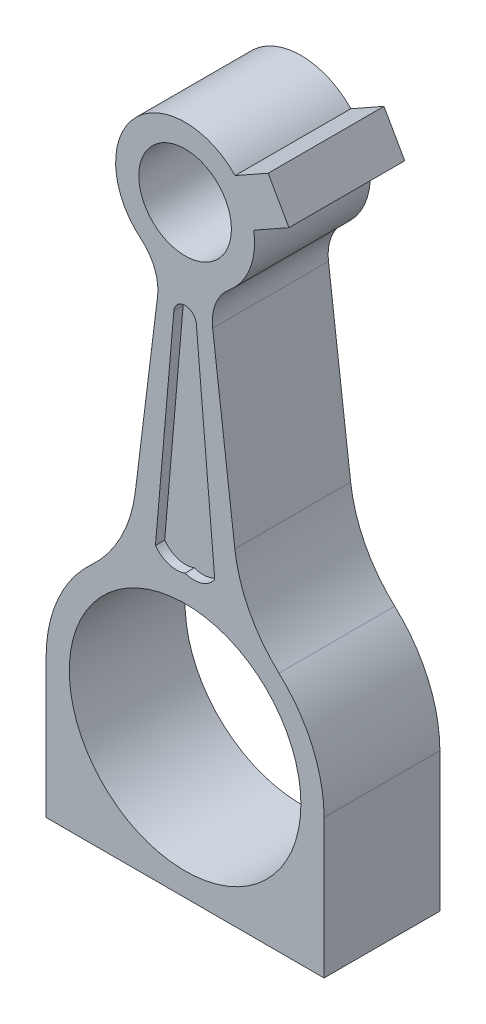
SolidWorks part; units mm, degrees
ref_plane "Front Plane" through (0, 0, 0) normal (0, 0, 1) x (1, 0, 0)
ref_plane "Top Plane" through (0, 0, 0) normal (0, 1, 0) x (1, 0, 0)
ref_plane "Right Plane" through (0, 0, 0) normal (1, 0, 0) x (0, 0, -1)
sketch "Sketch1" plane through (0, 0, 0) normal (0, 0, 1) x (1, 0, 0)
  line L0 (0, 0) -> (0, 100) construction
  line L1 (-5.9496, 79.4649) -> (-10.7353, 40.5936)
  line L2 (5.9496, 79.4649) -> (10.7353, 40.5936)
  line L3 (10.7954, 110.4144) -> (17.9357, 114.4279)
  line L5 (-30, 0) -> (-30, -30)
  line L6 (-30, -30) -> (30, -30)
  line L7 (30, 0) -> (30, -30)
  line L9 (17.9357, 114.4279) -> (22.4152, 106.4804)
  line L10 (14.8349, 102.2196) -> (22.4152, 106.4804)
  circle A0 centre (0, 0) radius 25
  arc A1 (-20.2553, 22.1297) -> (-30, 0) centre (0, 0) ccw
  circle A2 centre (0, 100) radius 10
  arc A3 (9.5248, 88.4121) -> (14.8349, 102.2196) centre (0, 100) ccw
  arc A4 (-5.9496, 79.4649) -> (-9.5248, 88.4121) centre (-15.8746, 80.6869) ccw
  arc A5 (-10.7353, 40.5936) -> (-20.2553, 22.1297) centre (-40.5105, 44.2594) cw
  arc A6 (10.7353, 40.5936) -> (20.2553, 22.1297) centre (40.5105, 44.2594) ccw
  arc A7 (5.9496, 79.4649) -> (9.5248, 88.4121) centre (15.8746, 80.6869) cw
  arc A8 (30, 0) -> (20.2553, 22.1297) centre (0, 0) ccw
  arc A9 (10.7954, 110.4144) -> (-9.5248, 88.4121) centre (0, 100) ccw
  dimension "D1" = 50
  dimension "D2" = 30
  dimension "D4" = 20
  dimension "D5" = 30
  dimension "D6" = 10
  dimension "D7" = 30
  dimension "D3" = 100
  dimension "D8" = 60
extrude "Boss-Extrude1" add sketch "Sketch1" along normal blind 25
sketch "Sketch2" plane through (0, 0, 25) normal (0, 0, 1) x (1, 0, 0)
  line L0 (-2.424, 78.5189) -> (-6.4034, 32.6767)
  line L1 (0, 93.5568) -> (0, 17.9011) construction
  line L2 (2.424, 78.5189) -> (6.4034, 32.6767)
  arc A0 (-6.4034, 32.6767) -> (0, 30.677) centre (-1.8817, 35.9038) ccw
  arc A1 (-2.424, 78.5189) -> (2.424, 78.5189) centre (0, 78.3083) cw
  arc A2 (6.4034, 32.6767) -> (0, 30.677) centre (1.8817, 35.9038) cw
  point P9 (0, 78.5189)
  point P10 (0, 30.677)
  point P11 (0, 0)
  point P12 (-6.4034, 32.6767)
extrude "Cut-Extrude1" cut sketch "Sketch2" against normal blind 2
